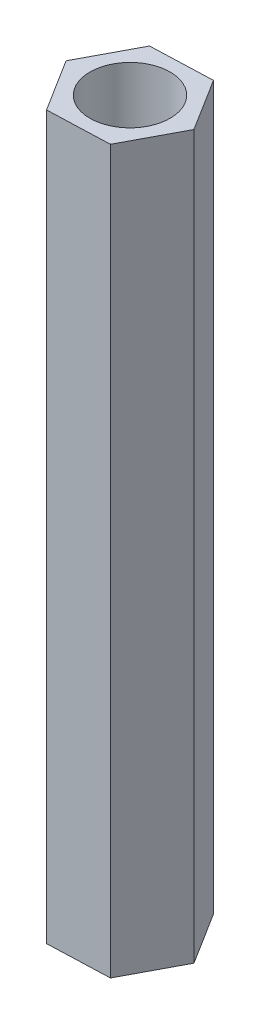
SolidWorks part; units mm, degrees
material "黄铜"
ref_plane "前视基准面" through (0, 0, 0) normal (0, 0, 1) x (1, 0, 0)
ref_plane "上视基准面" through (0, 0, 0) normal (0, 1, 0) x (1, 0, 0)
ref_plane "右视基准面" through (0, 0, 0) normal (1, 0, 0) x (0, 0, -1)
sketch "草图1" plane through (0, 0, 0) normal (0, 1, 0) x (1, 0, 0)
  line L1 (1.0818, 2.0403) -> (-1.2261, 1.9571)
  line L2 (-1.2261, 1.9571) -> (-2.3079, -0.0833)
  line L3 (-2.3079, -0.0833) -> (-1.0818, -2.0403)
  line L4 (-1.0818, -2.0403) -> (1.2261, -1.9571)
  line L5 (1.2261, -1.9571) -> (2.3079, 0.0833)
  line L6 (2.3079, 0.0833) -> (1.0818, 2.0403)
  circle A0 centre (0, 0) radius 1.5
  circle A1 centre (0, 0) radius 2 construction
  dimension "D1" = 3
  dimension "D2" = 4
extrude "凸台-拉伸1" add sketch "草图1" along normal blind 27
